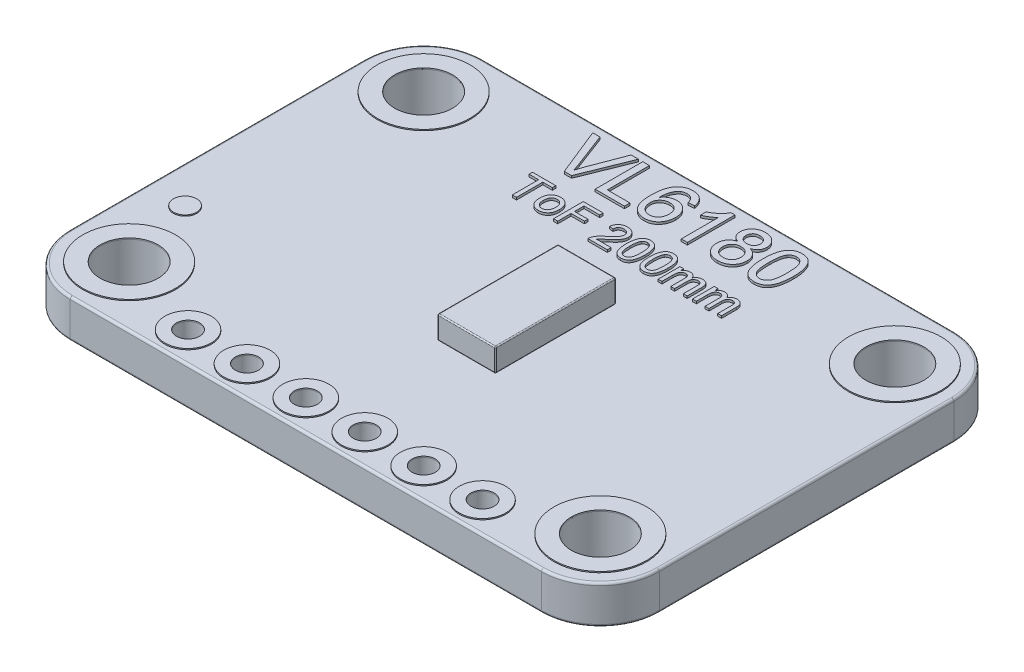
SolidWorks part; units mm, degrees
other "Camera1"
ref_plane "Front Plane" through (0, 0, 0) normal (0, 0, 1) x (1, 0, 0)
ref_plane "Top Plane" through (0, 0, 0) normal (0, 1, 0) x (1, 0, 0)
ref_plane "Right Plane" through (0, 0, 0) normal (1, 0, 0) x (0, 0, -1)
sketch "Sketch1" plane through (0, 0, 0) normal (0, 1, 0) x (1, 0, 0)
  line L0 (12.7, 17.78) -> (12.7, 0) construction
  line L1 (2.54, 0) -> (22.86, 0)
  line L2 (0, 2.54) -> (0, 15.24)
  line L3 (2.54, 17.78) -> (22.86, 17.78)
  line L4 (25.4, 2.54) -> (25.4, 15.24)
  line L5 (0, 8.89) -> (25.4, 8.89) construction
  line L6 (6.35, 1.27) -> (19.685, 1.27) construction
  line L7 (9.525, 19.05) -> (17.145, 19.05) construction
  circle A0 centre (2.54, 2.54) radius 1.25
  arc A1 (22.86, 0) -> (25.4, 2.54) centre (22.86, 2.54) ccw
  arc A2 (22.86, 17.78) -> (25.4, 15.24) centre (22.86, 15.24) cw
  arc A3 (0, 15.24) -> (2.54, 17.78) centre (2.54, 15.24) cw
  arc A4 (2.54, 0) -> (0, 2.54) centre (2.54, 2.54) cw
  circle A5 centre (2.54, 15.24) radius 1.25
  circle A6 centre (22.86, 2.54) radius 1.25
  circle A7 centre (22.86, 15.24) radius 1.25
  circle A8 centre (19.05, 1.27) radius 0.5
  circle A9 centre (16.51, 1.27) radius 0.5
  circle A10 centre (13.97, 1.27) radius 0.5
  circle A11 centre (11.43, 1.27) radius 0.5
  circle A12 centre (8.89, 1.27) radius 0.5
  circle A13 centre (6.35, 1.27) radius 0.5
  point P15 (25.4, 17.78)
  point P18 (0, 17.78)
  point P21 (0, 0)
  dimension "D3" = 2.5
  dimension "D4" = 2.54
  dimension "D5" = 2.54
  dimension "D6" = 2.54
  dimension "D7" = 1
  dimension "D10" = 6.35
  dimension "D1" = 17.78
  dimension "D2" = 25.4
  dimension "D8" = 1.27
  dimension "D11" = 6.35
  dimension "D13" = 19.05
  dimension "D12" = 6
extrude "Boss-Extrude1" add sketch "Sketch1" along normal blind 1.65
sketch "Sketch2" plane through (0, 1.65, 0) normal (0, 1, 0) x (1, 0, 0)
  line L0 (13.335, 11.49) -> (13.335, 6.29) construction
  line L1 (12.085, 11.49) -> (14.585, 11.49)
  line L2 (12.085, 11.49) -> (12.085, 6.29)
  line L3 (12.085, 6.29) -> (14.585, 6.29)
  line L4 (14.585, 11.49) -> (14.585, 6.29)
  line L5 (12.085, 8.89) -> (14.585, 8.89) construction
  line L7 (0, 15.24) -> (0, 2.54) construction
  point P8 (13.335, 8.89)
  point P9 (0, 8.89)
  dimension "D1" = 5.2
  dimension "D2" = 2.5
  dimension "D4" = 13.335
extrude "BNO055_IC" add sketch "Sketch2" along normal blind 1 separate body
fillet "Fillet1" radius 0.1 16 edges at (0.7439, 0, -0.7439) (0, 0, -8.89) (0.7439, 0, -17.0361) (12.7, 0, -17.78) (24.6561, 0, -17.0361) (25.4, 0, -8.89) (24.6561, 0, -0.7439) (0.7439, 1.65, -0.7439) (0, 1.65, -8.89) (0.7439, 1.65, -17.0361) (12.7, 1.65, -17.78) (24.6561, 1.65, -17.0361) (25.4, 1.65, -8.89) (24.6561, 1.65, -0.7439) (12.7, 0, 0) (12.7, 1.65, 0)
fillet "Fillet2" radius 0.05 12 edges at (13.335, 1.65, -11.49) (14.585, 2.15, -11.49) (14.585, 1.65, -8.89) (14.585, 2.15, -6.29) (13.335, 1.65, -6.29) (12.085, 2.15, -11.49) (12.085, 2.15, -6.29) (12.085, 1.65, -8.89) (13.335, 2.65, -11.49) (14.585, 2.65, -8.89) (13.335, 2.65, -6.29) (12.085, 2.65, -8.89)
sketch "Sketch16" plane through (0, 1.65, 0) normal (0, 1, 0) x (1, 0, 0)
  line L0 (2.54, 0) -> (22.86, 0) construction
  line L1 (0, 15.24) -> (0, 2.54) construction
  circle A0 centre (2.54, 2.54) radius 1.25
  circle A1 centre (2.54, 2.54) radius 2
  circle A2 centre (2.54, 15.24) radius 2
  circle A3 centre (2.54, 15.24) radius 1.25
  circle A4 centre (22.86, 15.24) radius 1.25
  circle A5 centre (22.86, 15.24) radius 2
  circle A6 centre (22.86, 2.54) radius 1.25
  circle A7 centre (22.86, 2.54) radius 2
  circle A8 centre (19.05, 1.27) radius 0.5
  circle A9 centre (19.05, 1.27) radius 1
  circle A10 centre (16.51, 1.27) radius 0.5
  circle A11 centre (16.51, 1.27) radius 1
  circle A12 centre (13.97, 1.27) radius 0.5
  circle A13 centre (13.97, 1.27) radius 1
  circle A14 centre (11.43, 1.27) radius 0.5
  circle A15 centre (11.43, 1.27) radius 1
  circle A16 centre (8.89, 1.27) radius 0.5
  circle A17 centre (8.89, 1.27) radius 1
  circle A18 centre (6.35, 1.27) radius 0.5
  circle A19 centre (6.35, 1.27) radius 1
  circle A28 centre (1.651, 5.842) radius 0.5
  dimension "D1" = 4
  dimension "D2" = 2.5
  dimension "D3" = 4
  dimension "D4" = 2.5
  dimension "D5" = 2.5
  dimension "D6" = 4
  dimension "D7" = 2.5
  dimension "D8" = 4
  dimension "D9" = 2
  dimension "D10" = 1
  dimension "D15" = 1
  dimension "D16" = 5.842
  dimension "D17" = 1.651
  dimension "D11" = 6
extrude "Boss-Extrude10" add sketch "Sketch16" along normal blind 0.05 separate body
ref_plane "Plane9" through (0, 0.825, 0) normal (0, 1, 0) x (1, 0, 0)
mirror "Mirror1" about plane through (0, 0.825, 0) normal (0, 1, 0) of "Boss-Extrude10"
sketch "Sketch22" plane through (0, 1.65, 0) normal (0, 1, 0) x (1, 0, 0)
  line L0 (12.7, 17.68) -> (12.7, 0.1) construction
  line L1 (22.86, 17.68) -> (2.54, 17.68) construction
  line L2 (2.54, 0.1) -> (22.86, 0.1) construction
  line L3 (2.54, 15.24) -> (22.86, 15.24) construction
  line L4 (2.54, 13.24) -> (22.86, 13.24) construction
  circle A1 centre (2.54, 15.24) radius 2 construction
  text T0 "VL6180\r\n" font "Arial" height in points 8
  text T1 "ToF 200mm\r\n" font "Arial" height in points 5
  point P9 (12.7, 15.24)
  point P14 (12.7, 13.24)
extrude "Boss-Extrude14" add sketch "Sketch22" along normal blind 0.1
